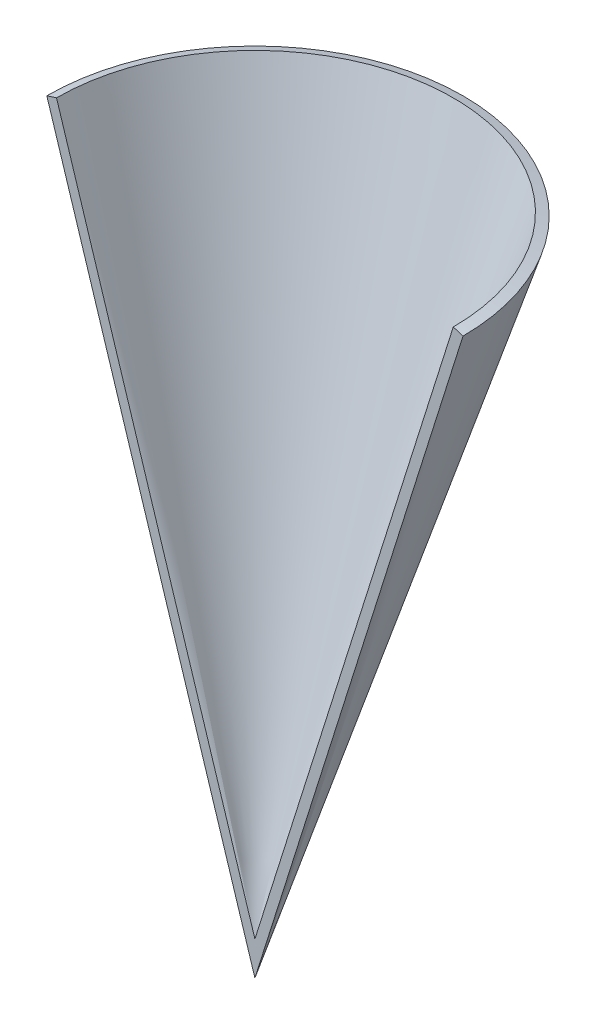
SolidWorks part; units mm, degrees
ref_plane "Alzado" through (0, 0, 0) normal (0, 0, 1) x (1, 0, 0)
ref_plane "Planta" through (0, 0, 0) normal (0, 1, 0) x (1, 0, 0)
ref_plane "Vista lateral" through (0, 0, 0) normal (1, 0, 0) x (0, 0, -1)
sketch "Croquis1" plane through (0, 0, 0) normal (0, 0, 1) x (1, 0, 0)
  line L0 (0, 0) -> (0, 6.651)
  line L1 (0, 6.651) -> (39.0283, 130.4331)
  line L2 (39.0283, 130.4331) -> (40.9358, 129.8317)
  line L3 (40.9358, 129.8317) -> (0, 0)
  line L4 (-39.0283, 130.4331) -> (-40.9358, 129.8317) construction
  line L5 (0, 6.651) -> (-39.0283, 130.4331) construction
  line L6 (-40.9358, 129.8317) -> (0, 0) construction
  ellipse E0 centre (0, 74.8317) end of major axis (0, 99.8317) minor radius 20 construction
  point P12 (0, 0)
  dimension "D1" = 2
  dimension "D2" = 40
  dimension "D3" = 50
  dimension "D4" = 30
  dimension "D5" = 35
revolve "Revolución1" add sketch "Croquis1" angle 180 about L0
